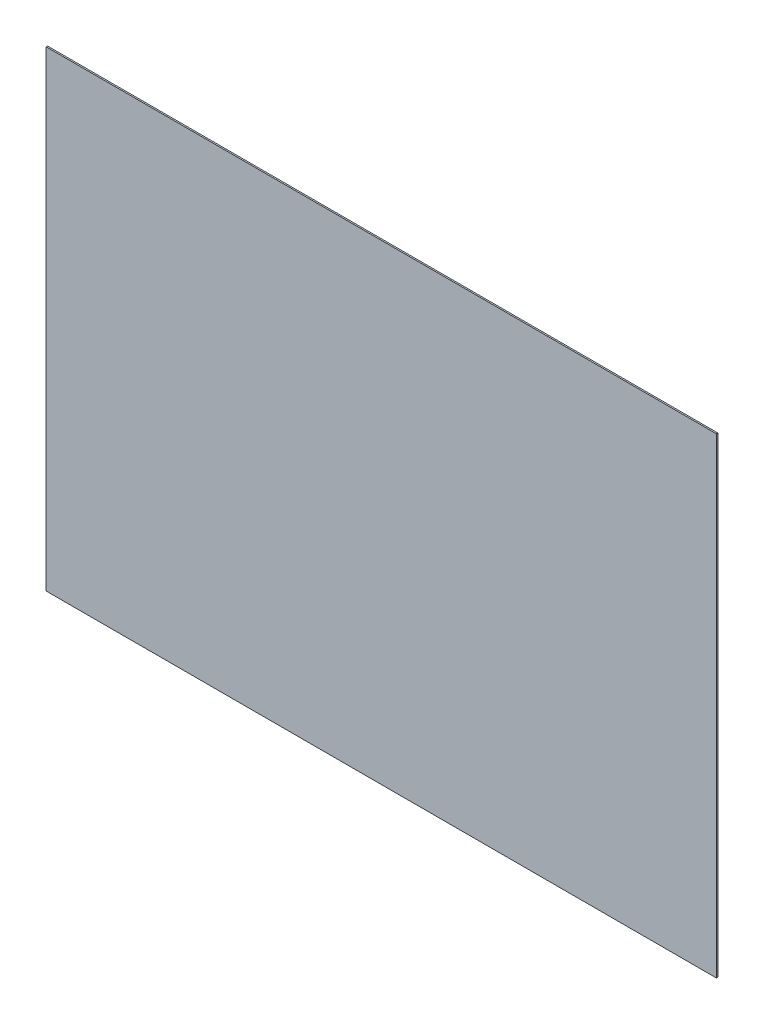
SolidWorks part; units mm, degrees
material "Alloy Steel"
ref_plane "Front Plane" through (0, 0, 0) normal (0, 0, 1) x (1, 0, 0)
ref_plane "Top Plane" through (0, 0, 0) normal (0, 1, 0) x (1, 0, 0)
ref_plane "Right Plane" through (0, 0, 0) normal (1, 0, 0) x (0, 0, -1)
sketch "Sketch1" plane through (0, 0, 0) normal (0, 0, 1) x (1, 0, 0)
  line L1 (-415.1996, 254.2542) -> (54.8004, 254.2542)
  line L2 (-415.1996, 254.2542) -> (-415.1996, -76.2458)
  line L3 (-415.1996, -76.2458) -> (54.8004, -76.2458)
  line L4 (54.8004, 254.2542) -> (54.8004, -76.2458)
  line L5 (-415.1996, 254.2542) -> (54.8004, -76.2458) construction
  line L6 (-415.1996, -76.2458) -> (54.8004, 254.2542) construction
  point P0 (-180.1996, 89.0042)
  dimension "D1" = 470
  dimension "D2" = 330.5
extrude "Boss-Extrude1" add sketch "Sketch1" along normal blind 1
